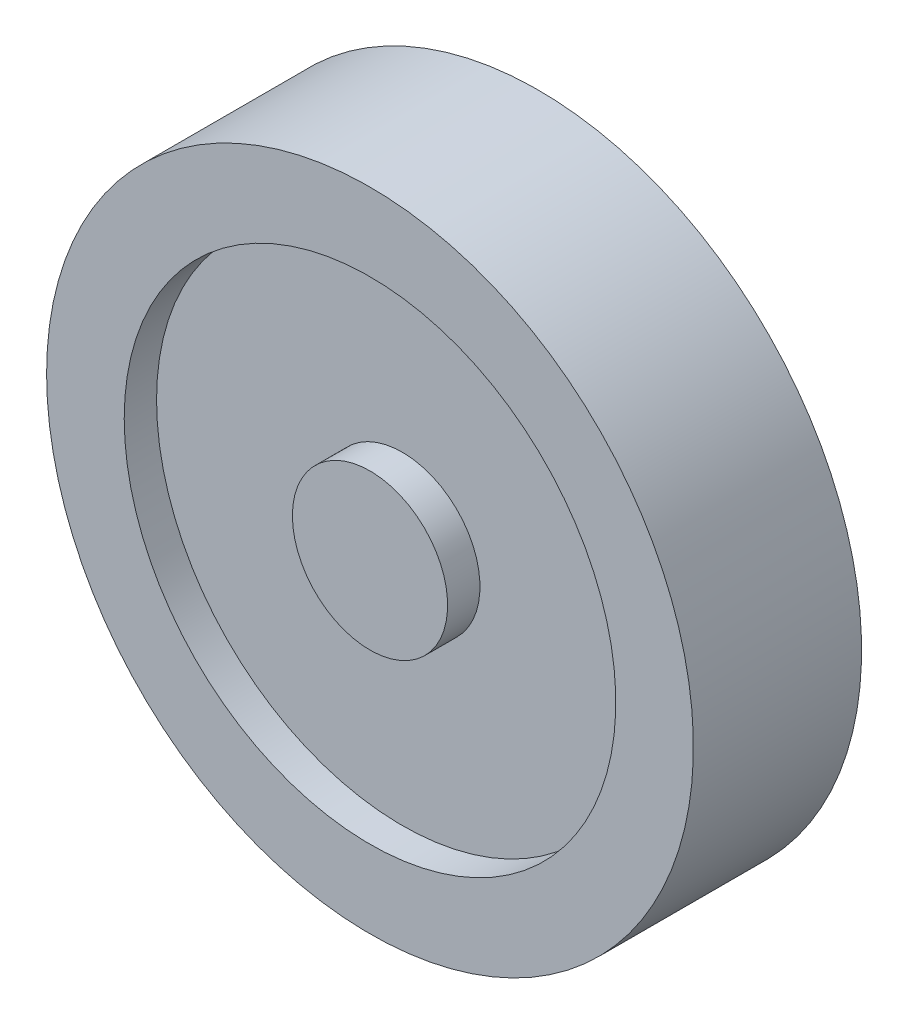
SolidWorks part; units mm, degrees
ref_plane "Front Plane" through (0, 0, 0) normal (0, 0, 1) x (1, 0, 0)
ref_plane "Top Plane" through (0, 0, 0) normal (0, 1, 0) x (1, 0, 0)
ref_plane "Right Plane" through (0, 0, 0) normal (1, 0, 0) x (0, 0, -1)
sketch "SK_Wheel" plane through (0, 0, 0) normal (0, 1, 0) x (1, 0, 0)
  line L0 (0, 13) -> (12, 13)
  line L1 (12, 13) -> (12, 8)
  line L2 (12, 8) -> (38, 8)
  line L3 (38, 8) -> (38, 13)
  line L4 (38, 13) -> (50, 13)
  line L5 (50, 13) -> (50, -13)
  line L6 (50, -13) -> (38, -13)
  line L7 (38, -13) -> (38, -8)
  line L8 (38, -8) -> (12, -8)
  line L9 (12, -8) -> (12, -13)
  line L10 (12, -13) -> (0, -13)
  line L11 (0, -13) -> (0, 13)
  line L12 (0, 18) -> (0, -18) construction
revolve "Wheel" add sketch "SK_Wheel" angle 360 about L12
